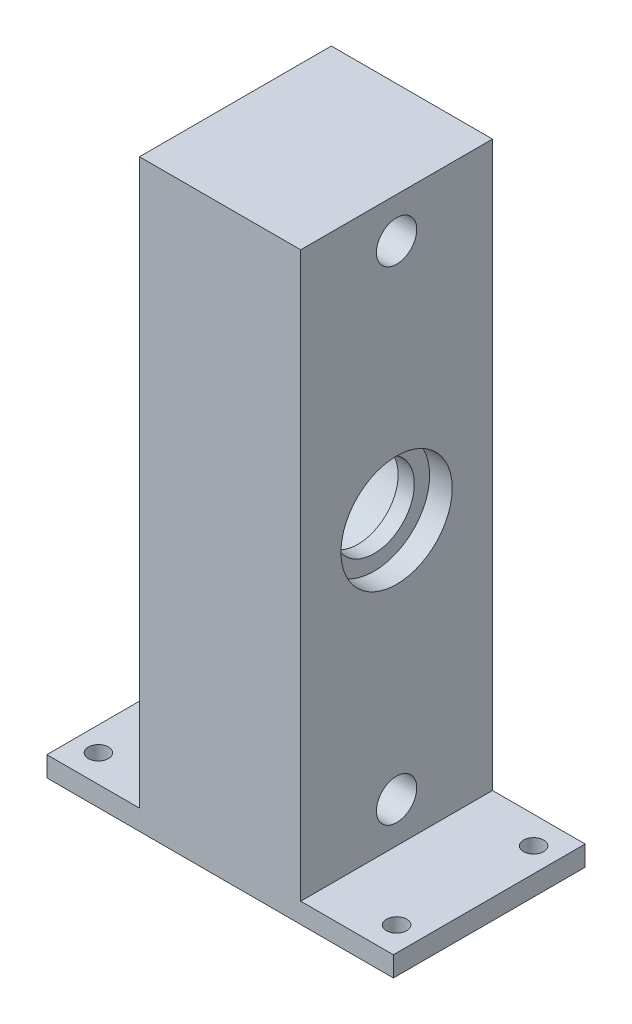
SolidWorks part; units mm, degrees
ref_plane "Front Plane" through (0, 0, 0) normal (0, 0, 1) x (1, 0, 0)
ref_plane "Top Plane" through (0, 0, 0) normal (0, 1, 0) x (1, 0, 0)
ref_plane "Right Plane" through (0, 0, 0) normal (1, 0, 0) x (0, 0, -1)
sketch "Sketch1" plane through (0, 0, 0) normal (0, 0, 1) x (1, 0, 0)
  line L1 (-12.7, 44.45) -> (12.7, 44.45)
  line L2 (-12.7, 44.45) -> (-12.7, -44.45)
  line L3 (-12.7, -44.45) -> (12.7, -44.45)
  line L4 (12.7, 44.45) -> (12.7, -44.45)
  point P5 (0, 44.45)
  point P7 (-12.7, 0)
  dimension "D1" = 25.4
  dimension "D2" = 88.9
extrude "Boss-Extrude1" add sketch "Sketch1" along normal blind 30.226
sketch "Sketch2" plane through (12.7, 0, 0) normal (1, 0, 0) x (0, 0, -1)
  line L0 (0, 0) -> (-95.9488, 0) construction
  line L1 (-30.226, 44.45) -> (0, 44.45) construction
  circle A0 centre (-15.113, 38.1) radius 3.175
  circle A1 centre (-15.113, -38.1) radius 3.175
  point P11 (-15.113, 44.45)
  dimension "D1" = 6.35
  dimension "D2" = 76.2
extrude "Cut-Extrude1" cut sketch "Sketch2" against normal blind 12.7
sketch "Sketch3" plane through (12.7, 0, 0) normal (1, 0, 0) x (0, 0, -1)
  line L0 (-30.226, 44.45) -> (0, 44.45) construction
  circle A0 centre (-15.113, 0) radius 8.763
  point P5 (-15.113, 44.45)
  dimension "D1" = 17.526
extrude "Cut-Extrude2" cut sketch "Sketch3" against normal blind 3.556
sketch "Sketch4" plane through (9.144, 0, 0) normal (1, 0, 0) x (0, 0, -1)
  circle A0 centre (-15.113, 0) radius 10.795
  dimension "D1" = 21.59
extrude "Cut-Extrude3" cut sketch "Sketch4" against normal up to vertex
sketch "Sketch5" plane through (0, -44.45, 0) normal (0, -1, 0) x (1, 0, 0)
  line L0 (-12.7, 0) -> (12.7, 0) construction
  line L1 (-27.305, 30.226) -> (27.305, 30.226)
  line L2 (-27.305, 30.226) -> (-27.305, 0)
  line L3 (-27.305, 0) -> (27.305, 0)
  line L4 (27.305, 30.226) -> (27.305, 0)
  line L5 (-12.7, 30.226) -> (12.7, 30.226) construction
  line L6 (0, 0) -> (0, 41.1105) construction
  dimension "D1" = 54.61
extrude "Boss-Extrude2" add sketch "Sketch5" along normal blind 3.175
sketch "Sketch6" plane through (0, -47.625, 0) normal (0, -1, 0) x (1, 0, 0)
  line L0 (-27.305, 15.113) -> (27.305, 15.113) construction
  line L1 (-27.305, 30.226) -> (-27.305, 0) construction
  line L2 (27.305, 0) -> (27.305, 30.226) construction
  circle A0 centre (-23.495, 25.908) radius 1.5875
  circle A1 centre (-23.495, 4.318) radius 1.5875
  circle A2 centre (23.495, 4.318) radius 1.5875
  circle A3 centre (23.495, 25.908) radius 1.5875
  dimension "D1" = 3.175
  dimension "D2" = 21.59
  dimension "D3" = 21.59
  dimension "D4" = 3.81
  dimension "D5" = 3.81
extrude "Cut-Extrude4" cut sketch "Sketch6" against normal up to vertex (3.175 mm away)
sketch "Sketch8" plane through (9.144, 0, 0) normal (-1, 0, 0) x (0, 0, 1)
  circle A0 centre (15.113, 0) radius 6.35
  circle A1 centre (15.113, 0) radius 10.795 construction
  circle A2 centre (15.113, 0) radius 10.795
  dimension "D1" = 12.7
extrude "Boss-Extrude3" add sketch "Sketch8" along normal blind 2.54
sketch "Sketch9" plane through (-12.7, 0, 0) normal (-1, 0, 0) x (0, 0, 1)
  line L0 (15.113, 10.795) -> (15.113, -19.5108) construction
  line L1 (25.908, 0) -> (-7.2773, 0) construction
  circle A0 centre (15.113, 0) radius 10.795 construction
  circle A1 centre (15.113, 0) radius 10.795 construction
  circle A2 centre (27.443, 12.33) radius 1.7
  circle A3 centre (2.783, 12.33) radius 1.7
  circle A4 centre (2.783, -12.33) radius 1.7
  circle A5 centre (27.443, -12.33) radius 1.7
  circle A6 centre (2.783, 12.33) radius 2.462
  circle A7 centre (27.443, 12.33) radius 2.462
  circle A8 centre (27.443, -12.33) radius 2.462
  circle A9 centre (2.783, -12.33) radius 2.462
  dimension "D1" = 3.4
  dimension "D2" = 12.33
  dimension "D3" = 12.33
  dimension "D4" = 0.762
